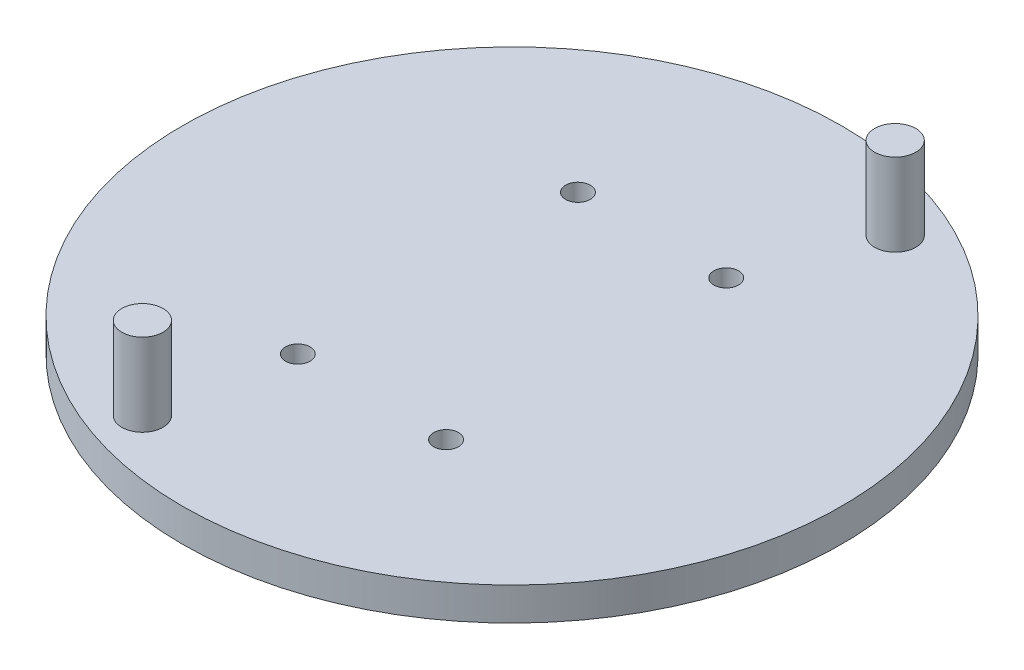
SolidWorks part; units mm, degrees
ref_plane "Front Plane" through (0, 0, 0) normal (0, 0, 1) x (1, 0, 0)
ref_plane "Top Plane" through (0, 0, 0) normal (0, 1, 0) x (1, 0, 0)
ref_plane "Right Plane" through (0, 0, 0) normal (1, 0, 0) x (0, 0, -1)
sketch "Sketch1" plane through (0, 0, 0) normal (0, 1, 0) x (1, 0, 0)
  line L1 (-9, 17) -> (9, 17) construction
  line L2 (-9, 17) -> (-9, -17) construction
  line L3 (-9, -17) -> (9, -17) construction
  line L4 (9, 17) -> (9, -17) construction
  line L5 (-9, 17) -> (9, -17) construction
  line L6 (-9, -17) -> (9, 17) construction
  circle A0 centre (0, 0) radius 40
  circle A1 centre (9, 17) radius 1.5
  circle A2 centre (-9, 17) radius 1.5
  circle A3 centre (-9, -17) radius 1.5
  circle A4 centre (9, -17) radius 1.5
  dimension "D1" = 80
  dimension "D4" = 3
  dimension "D5" = 3
  dimension "D6" = 3
  dimension "D7" = 3
  dimension "D2" = 34
  dimension "D3" = 18
extrude "Boss-Extrude1" add sketch "Sketch1" along normal blind 4
sketch "Sketch2" plane through (0, 4, 0) normal (0, 1, 0) x (1, 0, 0)
  line L0 (0, 0) -> (14.7916, 31.7208) construction
  line L1 (0, 0) -> (-11.9707, -32.8892) construction
  line L2 (0, 35) -> (0, -35) construction
  circle A0 centre (0, 0) radius 35 construction
  circle A1 centre (14.7916, 31.7208) radius 2.5
  circle A2 centre (-11.9707, -32.8892) radius 2.5
  point P9 (0, 0)
  point P10 (0, 17.6989)
  dimension "D1" = 5
  dimension "D2" = 5
  dimension "D4" = 20
  dimension "D5" = 70
  dimension "D3" = 25
extrude "Boss-Extrude2" add sketch "Sketch2" along normal blind 10
